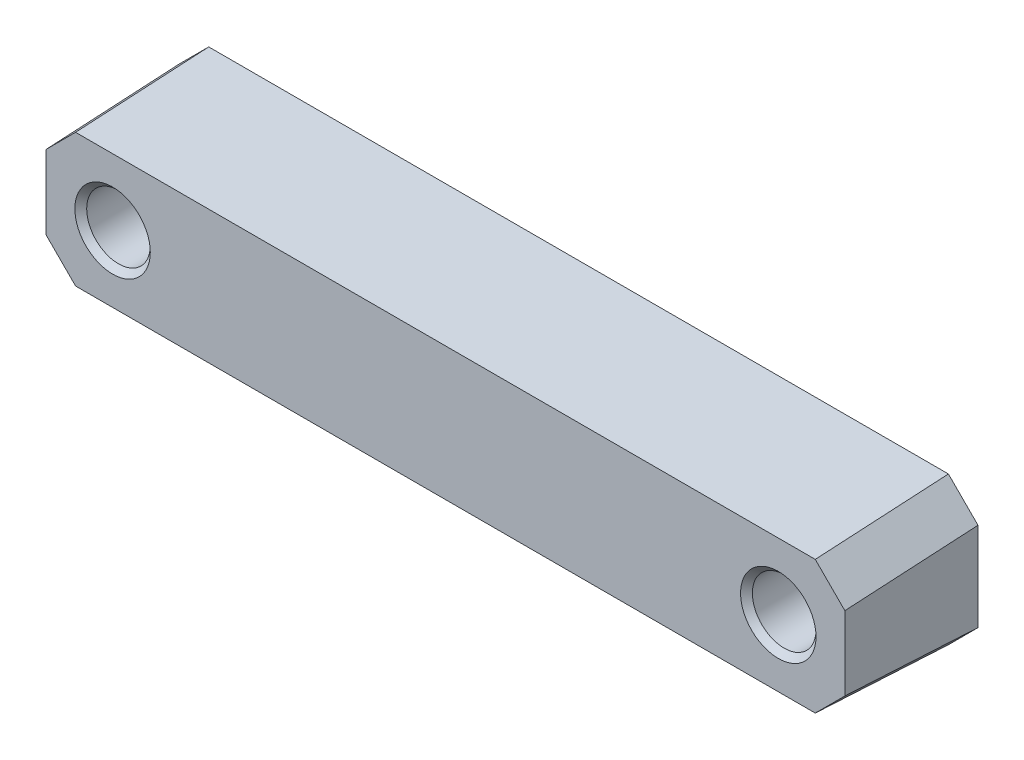
SolidWorks part; units mm, degrees
ref_plane "Front" through (0, 0, 0) normal (0, 0, 1) x (1, 0, 0)
ref_plane "Top" through (0, 0, 0) normal (0, 1, 0) x (1, 0, 0)
ref_plane "Right" through (0, 0, 0) normal (1, 0, 0) x (0, 0, -1)
sketch "Sketch1" plane through (0, 0, 0) normal (0, 0, 1) x (1, 0, 0)
  line L1 (0, 0) -> (54, 0)
  line L2 (0, 0) -> (0, 10)
  line L3 (0, 10) -> (54, 10)
  line L4 (54, 0) -> (54, 10)
  dimension "D1" = 10
  dimension "D2" = 54
ref_plane "Plane1" through (0, 0, 9) normal (0, 0, 1) x (1, 0, 0)
sketch "Sketch2" plane through (0, 0, 9) normal (0, 0, 1) x (1, 0, 0)
  line L0 (0, 0) -> (54, 0) construction
  line L1 (0, 9.5) -> (54, 9.5)
  line L2 (0, 9.5) -> (0, 0.5)
  line L3 (0, 0.5) -> (54, 0.5)
  line L4 (54, 9.5) -> (54, 0.5)
  line L5 (0, 0) -> (0, 10) construction
  dimension "D1" = 54
  dimension "D2" = 9
  dimension "D3" = 0.5
loft "Loft1" add profiles "Sketch1", "Sketch2"
sketch "Sketch3" plane through (0, 0, 0) normal (0, 0, -1) x (-1, 0, 0)
  line L0 (0, 0) -> (-54, 0) construction
  line L1 (-54, 0) -> (-54, 10) construction
  circle A0 centre (-49.5, 5) radius 2.15
  circle A1 centre (-4.5, 5) radius 2.15
  point P4 (0, 0)
  dimension "D4" = 4.3
  dimension "D1" = 5
  dimension "D2" = 4.5
  dimension "D3" = 45
extrude "Cut-Extrude1" cut sketch "Sketch3" against normal blind 10
chamfer "Chamfer1" distance 0.4 angle 45 4 edges at (2.35, 5, 0) (6.65, 5, 9) (47.35, 5, 0) (51.65, 5, 9)
chamfer "Chamfer2" distance 2 angle 45 2 edges
chamfer "Chamfer3" distance 2 angle 45 2 edges
